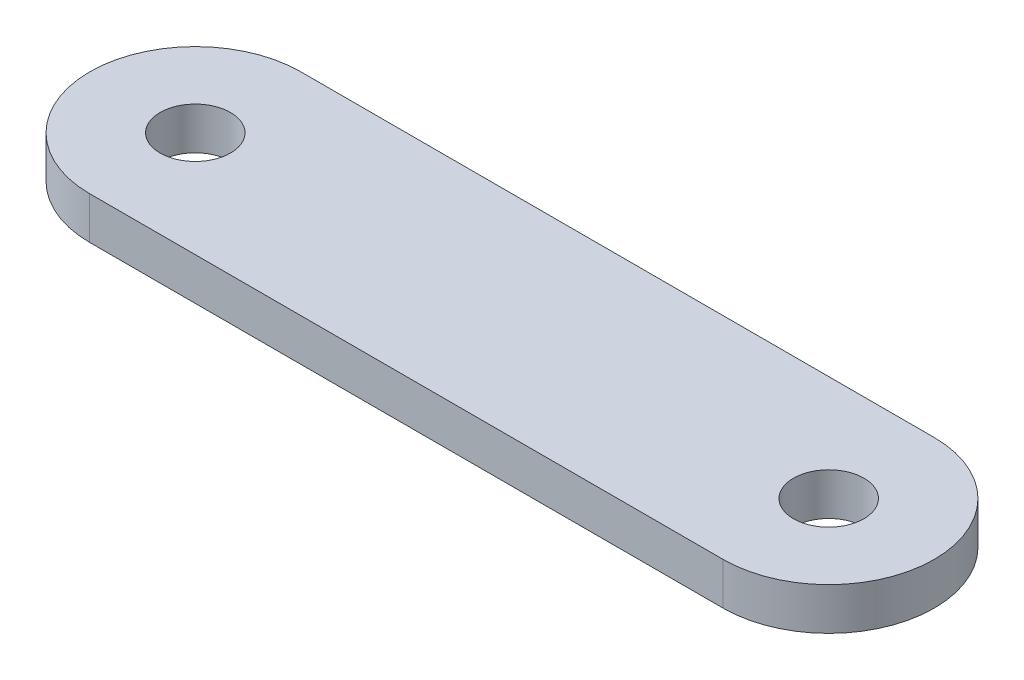
SolidWorks part; units mm, degrees
ref_plane "Front Plane" through (0, 0, 0) normal (0, 0, 1) x (1, 0, 0)
ref_plane "Top Plane" through (0, 0, 0) normal (0, 1, 0) x (1, 0, 0)
ref_plane "Right Plane" through (0, 0, 0) normal (1, 0, 0) x (0, 0, -1)
sketch "Sketch2" plane through (0, 0, 0) normal (0, 1, 0) x (1, 0, 0)
  line L1 (-45, 15) -> (45, 15)
  line L3 (-45, -15) -> (45, -15)
  arc A0 (-45, 15) -> (-45, -15) centre (-45, 0) ccw
  arc A1 (45, -15) -> (45, 15) centre (45, 0) ccw
  circle A2 centre (-45, 0) radius 5
  circle A3 centre (45, 0) radius 5
  point P0 (0, 0)
extrude "Boss-Extrude1" add sketch "Sketch2" along normal blind 6
